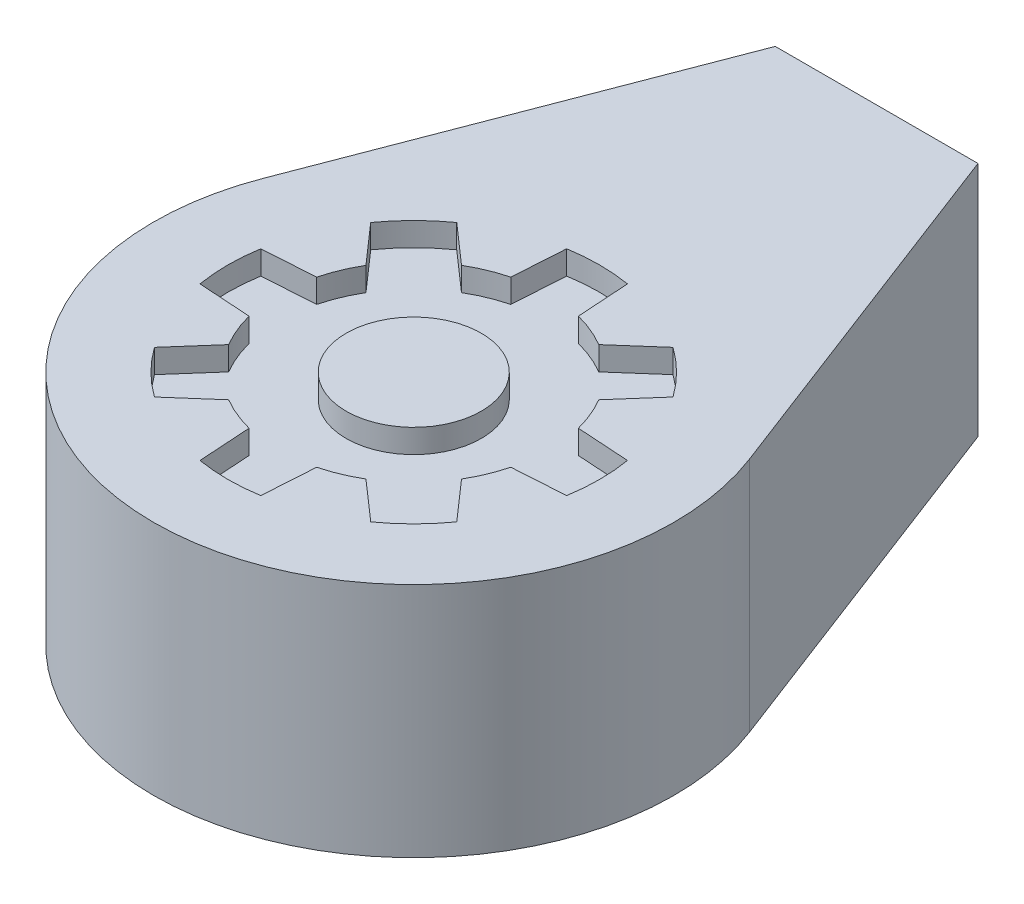
SolidWorks part; units mm, degrees
ref_plane "Front Plane" through (0, 0, 0) normal (0, 0, 1) x (1, 0, 0)
ref_plane "Top Plane" through (0, 0, 0) normal (0, 1, 0) x (1, 0, 0)
ref_plane "Right Plane" through (0, 0, 0) normal (1, 0, 0) x (0, 0, -1)
sketch "Sketch1" plane through (0, 0, 0) normal (0, 1, 0) x (1, 0, 0)
  line L1 (-2.5, -8.8013) -> (2.5, -8.8013)
  line L2 (-2.5, -8.8013) -> (-2.5, 8.8013)
  line L3 (-2.5, 8.8013) -> (2.5, 8.8013)
  line L4 (2.5, -8.8013) -> (2.5, 8.8013)
  line L5 (-2.5, -8.8013) -> (2.5, 8.8013) construction
  line L6 (-2.5, 8.8013) -> (2.5, -8.8013) construction
  circle A0 centre (0, 0) radius 6.7
  circle A1 centre (0, 0) radius 7.7
  dimension "D1" = 13.4
  dimension "D3" = 5
  dimension "D2" = 1
extrude "Boss-Extrude1" add sketch "Sketch1" along normal blind 6 contours L2 A1 A0 | L2 A1 L4 A0 | L4 A1 A0
sketch "Sketch2" plane through (0, 6, 0) normal (0, 1, 0) x (1, 0, 0)
  line L0 (0, 0) -> (0, 15.5073) construction
  line L1 (-3, 13.7) -> (3, 13.7)
  line L2 (3, 13.7) -> (7.191, 2.7531)
  line L3 (-3, 13.7) -> (-7.191, 2.7531)
  line L4 (-7.191, 2.7531) -> (7.191, 2.7531) construction
  circle A0 centre (0, 0) radius 7.7
  point P8 (0, 13.7)
  line M5 (-2.5, 6.2161) -> (-2.5, 7.2829)
  arc M6 (-2.5, 7.2829) -> (2.5, 7.2829) centre (0, 0) ccw
  line M7 (2.5, 7.2829) -> (2.5, 6.2161)
  arc M8 (2.5, 6.2161) -> (-2.5, 6.2161) centre (0, 0) cw
  dimension "D1" = 6
  dimension "D2" = 6
extrude "Boss-Extrude2" add sketch "Sketch2" along normal blind 1 contours A0 L2 L1 L3 M6 | M8 M5 M6 M7 | A0 M7 M5 M8
sketch "Sketch3" plane through (0, 6, 0) normal (0, -1, 0) x (1, 0, 0)
  line L0 (-3, -13.7) -> (-7.191, -2.7531)
  line L1 (-7.191, -2.7531) -> (-6.2571, -2.3955)
  line L2 (-4.9003, -5.9394) -> (-1.9292, -13.7) construction
  line L3 (-3, -13.7) -> (3, -13.7) construction
  line L4 (-1.9292, -13.7) -> (-3, -13.7)
  line L5 (-3, -13.7) -> (-7.191, -2.7531) construction
  line L6 (-2.5, -7.2829) -> (-1.9292, -13.7)
  line L7 (-2.5, -6.2161) -> (-2.5, -7.2829) construction
  line L8 (-6.2571, -2.3955) -> (-4.9003, -5.9394) construction
  line L9 (0, 0) -> (0, -17.6457) construction
  line L10 (1.9292, -13.7) -> (3, -13.7)
  line L11 (3, -13.7) -> (7.191, -2.7531)
  line L12 (2.5, -7.2829) -> (1.9292, -13.7)
  arc A0 (7.191, -2.7531) -> (2.5, -7.2829) centre (0, 0) cw
  arc A1 (2.5, -7.2829) -> (-2.5, -7.2829) centre (0, 0) ccw construction
  arc A2 (-7.191, -2.7531) -> (-2.5, -7.2829) centre (0, 0) ccw
  arc M8 (-2.5, -7.2829) -> (-7.191, -2.7531) centre (0, 0) cw
  line M9 (-7.191, -2.7531) -> (-3, -13.7)
  line M10 (-3, -13.7) -> (3, -13.7)
  line M11 (3, -13.7) -> (7.191, -2.7531)
  arc M12 (7.191, -2.7531) -> (2.5, -7.2829) centre (0, 0) cw
  dimension "D1" = 1
extrude "Boss-Extrude3" add sketch "Sketch3" along normal blind 6 contours L6 M8 M9 M10 | L12 M12 M10 M11
sketch "Sketch4" plane through (0, 7, 0) normal (0, 1, 0) x (1, 0, 0)
  line L0 (0, 0) -> (0, 5.5) construction
  line L1 (-0.9, 5.4259) -> (-1, 3.873)
  line L2 (0.9, 5.4259) -> (1, 3.873)
  line L3 (-1, 3.873) -> (1, 3.873) construction
  line L4 (0.9, 5.4259) -> (-0.9, 5.4259) construction
  line L5 (3.2003, 4.4731) -> (2.0315, 3.4457)
  line L6 (4.4731, 3.2003) -> (3.4457, 2.0315)
  line L7 (5.4259, 0.9) -> (3.873, 1)
  line L8 (5.4259, -0.9) -> (3.873, -1)
  line L9 (4.4731, -3.2003) -> (3.4457, -2.0315)
  line L10 (3.2003, -4.4731) -> (2.0315, -3.4457)
  line L11 (0.9, -5.4259) -> (1, -3.873)
  line L12 (-0.9, -5.4259) -> (-1, -3.873)
  line L13 (-3.2003, -4.4731) -> (-2.0315, -3.4457)
  line L14 (-4.4731, -3.2003) -> (-3.4457, -2.0315)
  line L15 (-5.4259, -0.9) -> (-3.873, -1)
  line L16 (-5.4259, 0.9) -> (-3.873, 1)
  line L17 (-4.4731, 3.2003) -> (-3.4457, 2.0315)
  line L18 (-3.2003, 4.4731) -> (-2.0315, 3.4457)
  circle A0 centre (0, 0) radius 4
  circle A1 centre (0, 0) radius 5.5
  point P40 (0, 0)
  dimension "D1" = 8
  dimension "D2" = 11
  dimension "D3" = 2
  dimension "D4" = 1.8
  dimension "D5" = 8
extrude "Cut-Extrude1" cut sketch "Sketch4" against normal blind 0.7 contours A0 | L18 A1 L17 A0 | L16 A1 L15 A0 | L14 A1 L13 A0 | L12 A1 L11 A0 | L10 A1 L9 A0 | L8 A1 L7 A0 | L6 A1 L5 A0 | L2 A1 L1 A0
sketch "Sketch5" plane through (0, 6.3, 0) normal (0, 1, 0) x (1, 0, 0)
  circle A0 centre (0, 0) radius 2
  dimension "D1" = 4
extrude "Boss-Extrude4" add sketch "Sketch5" along normal up to surface (0.7 mm away) up to face at (0, 7, 0)
